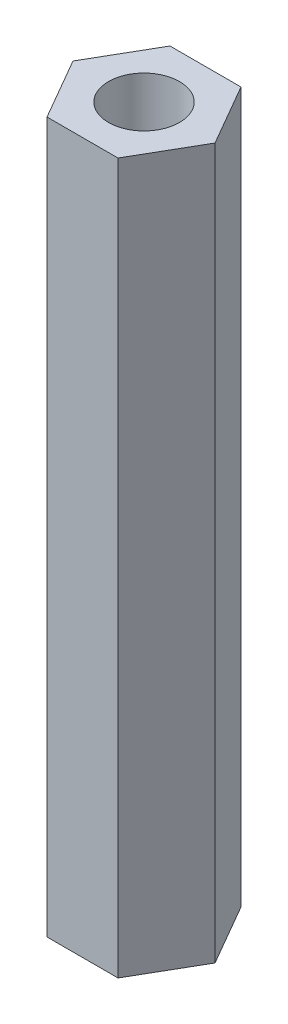
SolidWorks part; units mm, degrees
ref_plane "Front Plane" through (0, 0, 0) normal (0, 0, 1) x (1, 0, 0)
ref_plane "Top Plane" through (0, 0, 0) normal (0, 1, 0) x (1, 0, 0)
ref_plane "Right Plane" through (0, 0, 0) normal (1, 0, 0) x (0, 0, -1)
sketch "Sketch1" plane through (0, 0, 0) normal (0, 1, 0) x (1, 0, 0)
  line L1 (1.25, 2.1651) -> (-1.25, 2.1651)
  line L2 (-1.25, 2.1651) -> (-2.5, 0)
  line L3 (-2.5, 0) -> (-1.25, -2.1651)
  line L4 (-1.25, -2.1651) -> (1.25, -2.1651)
  line L5 (1.25, -2.1651) -> (2.5, 0)
  line L6 (2.5, 0) -> (1.25, 2.1651)
  circle A0 centre (0, 0) radius 2.1651 construction
  circle A1 centre (0, 0) radius 1.25
  dimension "D1" = 2.5
  dimension "D2" = 2.5
extrude "Boss-Extrude1" add sketch "Sketch1" along normal blind 25
